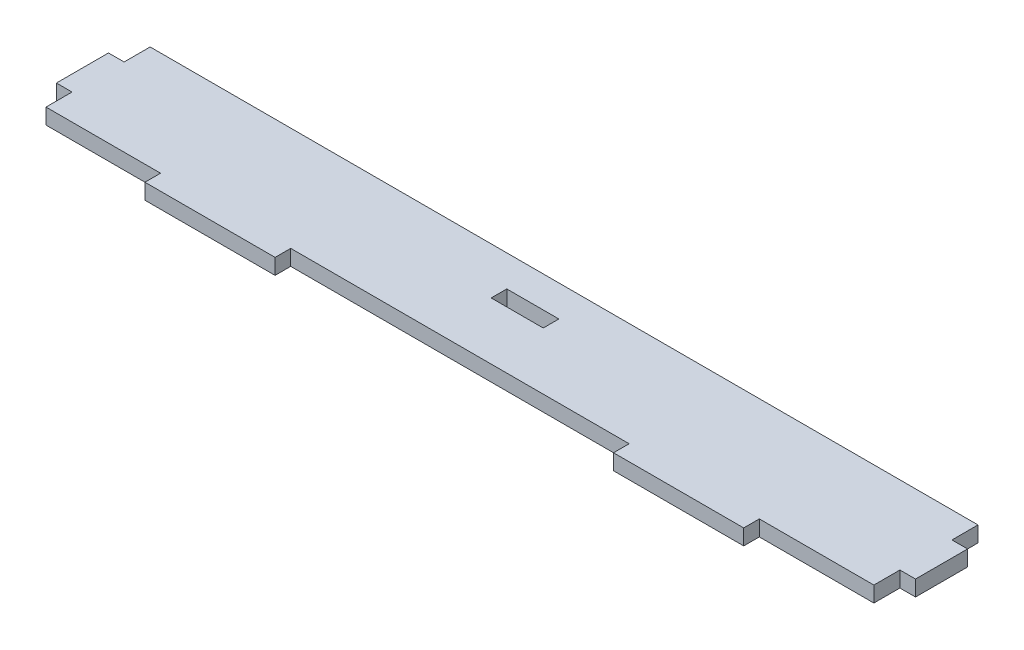
SolidWorks part; units mm, degrees
ref_plane "Front Plane" through (0, 0, 0) normal (0, 0, 1) x (1, 0, 0)
ref_plane "Top Plane" through (0, 0, 0) normal (0, 1, 0) x (1, 0, 0)
ref_plane "Right Plane" through (0, 0, 0) normal (1, 0, 0) x (0, 0, -1)
sketch "Sketch1" plane through (0, 0, 0) normal (0, 1, 0) x (1, 0, 0)
  line L0 (-79.5, 5) -> (-79.5, 10)
  line L1 (79.5, -10) -> (57.5, -10)
  line L2 (79.5, -10) -> (79.5, -5)
  line L3 (79.5, 10) -> (-79.5, 10)
  line L4 (-79.5, -10) -> (-79.5, -5)
  line L5 (79.5, -10) -> (-79.5, 10) construction
  line L6 (79.5, 10) -> (-79.5, -10) construction
  line L7 (-79.5, 5) -> (-82.5, 5)
  line L8 (-57.5, -10) -> (-79.5, -10)
  line L9 (-79.5, -5) -> (-82.5, -5)
  line L10 (-82.5, 5) -> (-82.5, -5)
  line L11 (79.5, 5) -> (82.5, 5)
  line L13 (79.5, -5) -> (82.5, -5)
  line L14 (82.5, 5) -> (82.5, -5)
  line L15 (32.5, -10) -> (-32.5, -10)
  line L16 (-57.5, -10) -> (-57.5, -13)
  line L17 (-57.5, -13) -> (-32.5, -13)
  line L18 (-32.5, -10) -> (-32.5, -13)
  line L19 (79.5, 5) -> (79.5, 10)
  line L20 (32.5, -10) -> (32.5, -13)
  line L21 (32.5, -13) -> (57.5, -13)
  line L22 (57.5, -10) -> (57.5, -13)
  line L23 (-5, 4) -> (5, 4)
  line L24 (-5, 4) -> (-5, 1)
  line L25 (-5, 1) -> (5, 1)
  line L26 (5, 4) -> (5, 1)
  line L27 (-5, 4) -> (5, 1) construction
  line L28 (-5, 1) -> (5, 4) construction
  point P0 (0, 0)
  point P22 (0, 2.5)
  dimension "D1" = 20
  dimension "D2" = 159
  dimension "D3" = 5
  dimension "D4" = 10
  dimension "D5" = 25
  dimension "D6" = 25
  dimension "D7" = 65
  dimension "D8" = 22
  dimension "D9" = 11
  dimension "D10" = 10
  dimension "D11" = 3
  dimension "D12" = 3
  dimension "D13" = 3
extrude "Boss-Extrude1" add sketch "Sketch1" along normal blind 3
